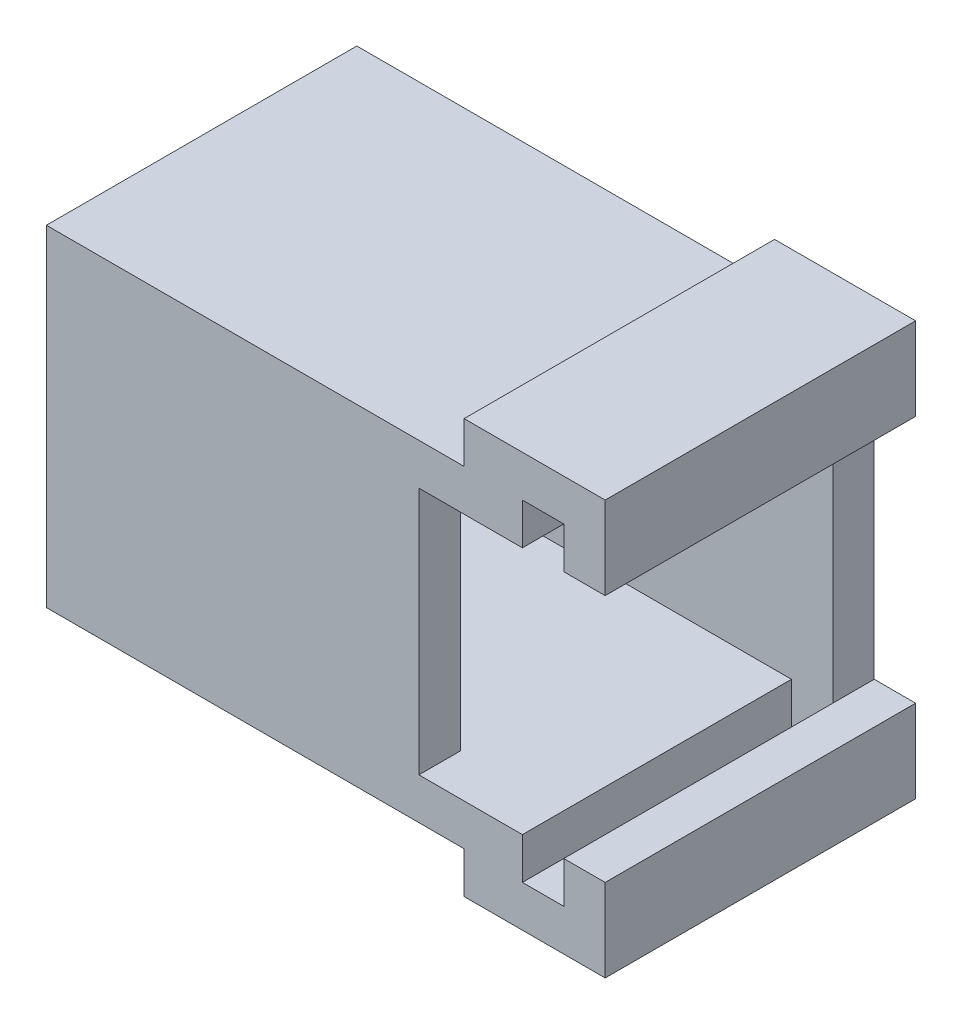
SolidWorks part; units mm, degrees
ref_plane "Alzado" through (0, 0, 0) normal (0, 0, 1) x (1, 0, 0)
ref_plane "Planta" through (0, 0, 0) normal (0, 1, 0) x (1, 0, 0)
ref_plane "Vista lateral" through (0, 0, 0) normal (1, 0, 0) x (0, 0, -1)
sketch "Croquis1" plane through (0, 0, 0) normal (0, 0, 1) x (1, 0, 0)
  line L1 (0, 0) -> (23, 0)
  line L2 (0, 0) -> (0, 16)
  line L3 (0, 16) -> (23, 16)
  line L4 (23, 0) -> (23, 16)
  dimension "D1" = 16
  dimension "D2" = 23
extrude "Saliente-Extruir1" add sketch "Croquis1" along normal blind 15
sketch "Croquis2" plane through (23, 0, 0) normal (1, 0, 0) x (0, 0, -1)
  line L0 (0, 0) -> (0, 16) construction
  line L1 (-13, 2) -> (-2, 2)
  line L2 (-13, 2) -> (-13, 14)
  line L3 (-13, 14) -> (-2, 14)
  line L4 (-2, 2) -> (-2, 14)
  line L5 (-15, 0) -> (-15, 16) construction
  line L6 (-15, 16) -> (0, 16) construction
  line L7 (-15, 0) -> (0, 0) construction
  dimension "D1" = 2
  dimension "D2" = 2
  dimension "D3" = 2
  dimension "D4" = 2
extrude "Cortar-Extruir1" cut sketch "Croquis2" against normal blind 21
sketch "Croquis4" plane through (0, 0, 0) normal (-1, 0, 0) x (0, 0, 1)
  line L0 (0, 0) -> (15, 16) construction
  line L1 (15, 16) -> (15, 0) construction
  line L2 (15, 16) -> (0, 16) construction
  circle A0 centre (7.5, 8) radius 4
  dimension "D1" = 8
extrude "Cortar-Extruir2" cut sketch "Croquis4" against normal blind 23
sketch "Croquis5" plane through (0, 0, 15) normal (0, 0, 1) x (1, 0, 0)
  line L0 (23, 0) -> (23, 16) construction
  line L1 (23, 2) -> (18, 2)
  line L2 (23, 2) -> (23, 14)
  line L3 (23, 14) -> (18, 14)
  line L4 (18, 2) -> (18, 14)
  line L5 (23, 16) -> (0, 16) construction
  line L6 (0, 0) -> (23, 0) construction
  dimension "D1" = 2
  dimension "D2" = 2
  dimension "D3" = 5
extrude "Cortar-Extruir3" cut sketch "Croquis5" against normal blind 2
sketch "Croquis6" plane through (0, 0, 15) normal (0, 0, 1) x (1, 0, 0)
  line L0 (20.1841, 16) -> (20.1841, 18)
  line L1 (23, 16) -> (0, 16) construction
  line L2 (20.1841, 18) -> (27, 18)
  line L3 (27, 18) -> (27, 14)
  line L4 (27, 14) -> (25, 14)
  line L5 (25, 14) -> (25, 16)
  line L6 (25, 16) -> (23, 16)
  line L7 (23, 14) -> (23, 16) construction
  line L8 (18, 8) -> (25, 8) construction
  line L9 (18, 14) -> (18, 2) construction
  line L10 (20.1841, 16) -> (23, 16)
  line L11 (20.1841, 0) -> (23, 0)
  line L12 (25, 0) -> (23, 0)
  line L13 (25, 2) -> (25, 0)
  line L14 (27, 2) -> (25, 2)
  line L15 (27, -2) -> (27, 2)
  line L16 (20.1841, -2) -> (27, -2)
  line L17 (20.1841, 0) -> (20.1841, -2)
  dimension "D1" = 2
  dimension "D2" = 2
  dimension "D3" = 2
  dimension "D4" = 4
  dimension "D5" = 6.8159
extrude "Saliente-Extruir2" add sketch "Croquis6" against normal blind 15
sketch "Croquis7" plane through (0, 0, 0) normal (0, 0, -1) x (-1, 0, 0)
  line L1 (-23, 0) -> (-25, 0)
  line L2 (-23, 0) -> (-23, 16)
  line L3 (-23, 16) -> (-25, 16)
  line L4 (-25, 0) -> (-25, 16)
extrude "Saliente-Extruir3" add sketch "Croquis7" against normal blind 2
